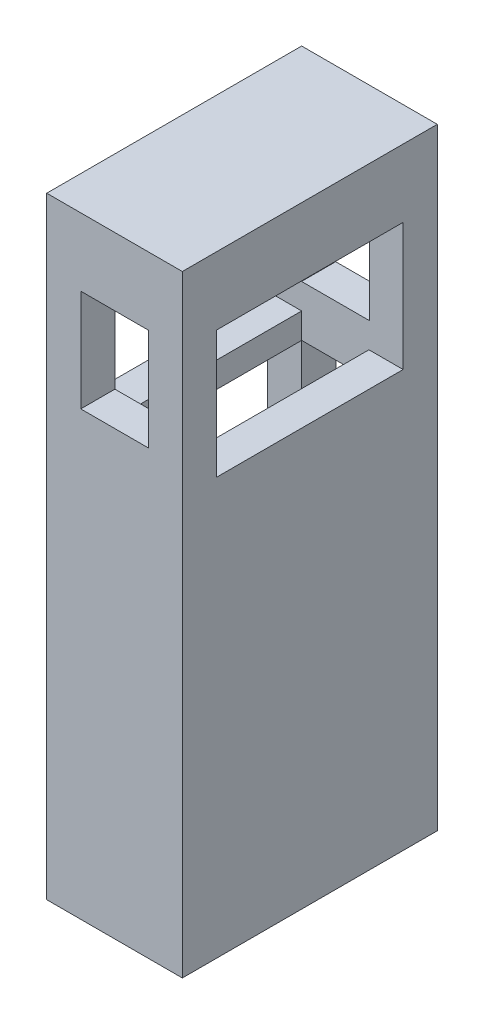
SolidWorks part; units mm, degrees
material "1023 Carbon Steel Sheet (SS)"
ref_plane "Front Plane" through (0, 0, 0) normal (0, 0, 1) x (1, 0, 0)
ref_plane "Top Plane" through (0, 0, 0) normal (0, 1, 0) x (1, 0, 0)
ref_plane "Right Plane" through (0, 0, 0) normal (1, 0, 0) x (0, 0, -1)
sketch "Sketch2" plane through (0, 0, 0) normal (0, 0, 1) x (1, 0, 0)
  line L1 (0, 0) -> (2660, 0)
  line L2 (0, 0) -> (0, 12000)
  line L3 (0, 12000) -> (2660, 12000)
  line L4 (2660, 0) -> (2660, 12000)
  dimension "D1" = 2660
  dimension "D2" = 12000
extrude "Boss-Extrude1" add sketch "Sketch2" along normal blind 5000 contours L2 L1 L4 L3
sketch "Sketch3" plane through (0, 0, 5000) normal (0, 0, 1) x (1, 0, 0)
  line L0 (0, 12000) -> (2660, 12000) construction
  line L1 (667.5, 10670) -> (1997.5, 10670)
  line L2 (667.5, 10670) -> (667.5, 8670)
  line L3 (667.5, 8670) -> (1997.5, 8670)
  line L4 (1997.5, 10670) -> (1997.5, 8670)
  line L6 (0, 0) -> (0, 12000) construction
  dimension "D1" = 1330
  dimension "D2" = 2000
  dimension "D3" = 667.5
  dimension "D4" = 1330
extrude "Cut-Extrude1" cut sketch "Sketch3" against normal blind 5000
sketch "Sketch4" plane through (2660, 0, 0) normal (1, 0, 0) x (0, 0, -1)
  line L0 (-5000, 12000) -> (0, 12000) construction
  line L1 (-4330, 10670) -> (-670, 10670)
  line L2 (-4330, 10670) -> (-4330, 8170)
  line L3 (-4330, 8170) -> (-670, 8170)
  line L4 (-670, 10670) -> (-670, 8170)
  line L5 (-5000, 0) -> (-5000, 12000) construction
  point P4 (-2500, 10670)
  dimension "D1" = 1330
  dimension "D2" = 2500
  dimension "D3" = 3660
  dimension "D4" = 670
extrude "Cut-Extrude2" cut sketch "Sketch4" against normal through all contours L2 L1 L4 L3
sketch "Sketch6" plane through (0, 8170, 0) normal (0, 1, 0) x (1, 0, 0)
  line L0 (0, -4330) -> (2660, -4330) construction
  line L1 (1990, -4330) -> (670, -4330)
  line L2 (1990, -4330) -> (1990, -670)
  line L3 (1990, -670) -> (670, -670)
  line L4 (670, -4330) -> (670, -670)
  line L5 (2660, -4330) -> (2660, -670) construction
  line L6 (0, -4330) -> (0, -670) construction
  line L7 (0, -670) -> (2660, -670) construction
  dimension "D1" = 670
  dimension "D2" = 670
  dimension "D3" = 0
extrude "Cut-Extrude3" cut sketch "Sketch6" against normal blind 2660
sketch "Sketch7" plane through (0, 0, 0) normal (0, 0, -1) x (-1, 0, 0)
  line L1 (-1990, 7670) -> (-667.5, 7670)
  line L2 (-1990, 7670) -> (-1990, 5010)
  line L3 (-1990, 5010) -> (-667.5, 5010)
  line L4 (-667.5, 7670) -> (-667.5, 5010)
  line L5 (-667.5, 8670) -> (-1997.5, 8670) construction
  line L6 (-2660, 0) -> (-2660, 12000) construction
  dimension "D1" = 0
  dimension "D2" = 1000
  dimension "D3" = 2660
  dimension "D4" = 670
extrude "Cut-Extrude6" cut sketch "Sketch7" against normal blind 4269 and the other way through all
sketch "Sketch8" plane through (0, 0, 4269) normal (0, 0, -1) x (-1, 0, 0)
  line L1 (-1990, 5510) -> (-667.5, 5510)
  line L2 (-1990, 5510) -> (-1990, 5010)
  line L3 (-1990, 5010) -> (-667.5, 5010)
  line L4 (-667.5, 5510) -> (-667.5, 5010)
extrude "Cut-Extrude7" cut sketch "Sketch8" against normal up to vertex (61 mm away)
sketch "Sketch11" plane through (667.5, 0, 0) normal (1, 0, 0) x (0, 0, -1)
  line L1 (-4269, 7670) -> (0, 7670)
  line L2 (-4269, 7670) -> (-4269, 5010)
  line L3 (-4269, 5010) -> (0, 5010)
  line L4 (0, 7670) -> (0, 5010)
extrude "Boss-Extrude2" add sketch "Sketch11" along normal up to vertex
sketch "Sketch12" plane through (667.5, 0, 0) normal (1, 0, 0) x (0, 0, -1)
  line L0 (-4269, 5510) -> (-4269, 5010) construction
  line L1 (-4330, 5510) -> (-4269, 5510)
  line L2 (-4330, 5510) -> (-4330, 5010)
  line L3 (-4330, 5010) -> (-4269, 5010)
  line L4 (-4269, 5510) -> (-4269, 5010)
extrude "Boss-Extrude3" add sketch "Sketch12" along normal up to vertex
sketch "Sketch13" plane through (2660, 0, 0) normal (1, 0, 0) x (0, 0, -1)
  line L0 (-4330, 10670) -> (-4330, 8170) construction
  line L1 (-670, 5010) -> (-4341.6515, 5010)
  line L2 (-670, 5010) -> (-670, 7670)
  line L3 (-670, 7670) -> (-4341.6515, 7670)
  line L4 (-4341.6515, 5010) -> (-4341.6515, 7670)
  line L5 (-670, 10670) -> (-670, 8170) construction
sketch "Sketch15" plane through (0, 0, 0) normal (0, 0, -1) x (-1, 0, 0)
sketch "Sketch16" plane through (670, 0, 0) normal (1, 0, 0) x (0, 0, -1)
sketch "Sketch17" plane through (0, 0, 0) normal (-1, 0, 0) x (0, 0, 1)
  line L1 (4330, 5010) -> (670, 5010)
  line L2 (4330, 5010) -> (4330, 7670)
  line L3 (4330, 7670) -> (670, 7670)
  line L4 (670, 5010) -> (670, 7670)
extrude "Cut-Extrude10" cut sketch "Sketch17" against normal up to vertex (670 mm away) contours L2 L1 L4 L3
sketch "Sketch18" plane through (0, 0, 0) normal (0, -1, 0) x (-1, 0, 0)
  line L0 (-2660, -5000) -> (-2660, 0) construction
  line L1 (-2160, -4500) -> (-500, -4500)
  line L2 (-2160, -4500) -> (-2160, -500)
  line L3 (-2160, -500) -> (-500, -500)
  line L4 (-500, -4500) -> (-500, -500)
  line L5 (0, 0) -> (-2660, 0) construction
  line L6 (0, -5000) -> (0, 0) construction
  line L7 (0, -5000) -> (-2660, -5000) construction
  dimension "D1" = 500
  dimension "D2" = 500
  dimension "D3" = 500
  dimension "D4" = 500
sketch "Sketch21" plane through (0, 10670, 0) normal (0, -1, 0) x (1, 0, 0)
  line L0 (0, 4330) -> (667.5, 4330) construction
  line L1 (200, 4330) -> (2460, 4330)
  line L2 (200, 4330) -> (200, 670)
  line L3 (200, 670) -> (2460, 670)
  line L4 (2460, 4330) -> (2460, 670)
  line L5 (1997.5, 670) -> (2660, 670) construction
  line L6 (0, 4330) -> (0, 670) construction
  line L7 (2660, 4330) -> (2660, 670) construction
  dimension "D1" = 200
  dimension "D2" = 200
extrude "Cut-Extrude12" cut sketch "Sketch21" against normal blind 1000
extrude "Cut-Extrude13" cut sketch "Sketch18" against normal blind 4500
